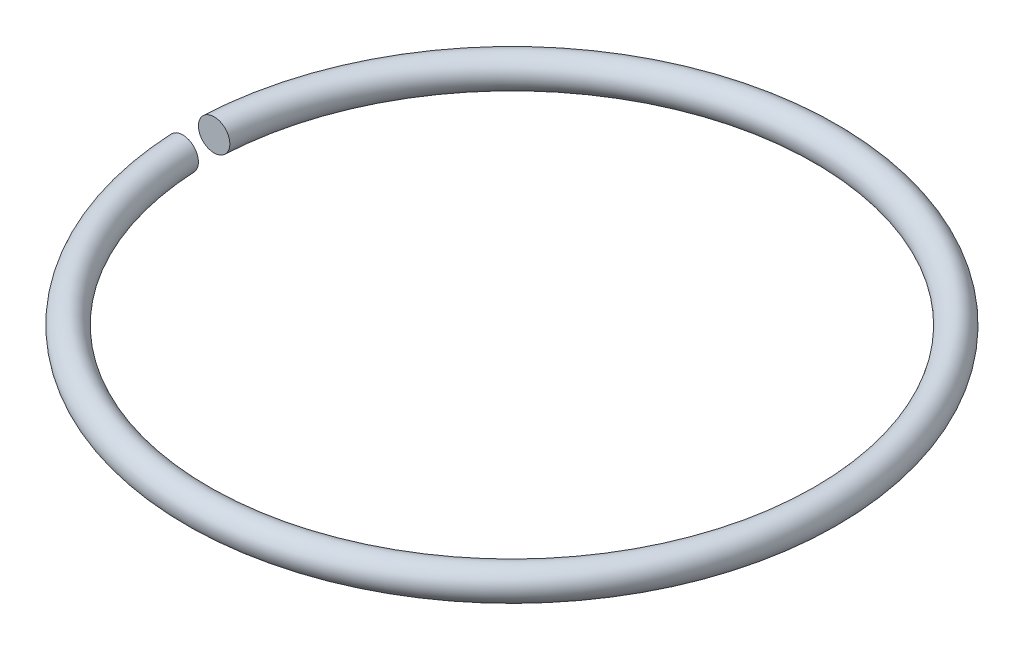
SolidWorks part; units mm, degrees
material "1.5805 (10NiCr5-4)"
ref_plane "Спереди" through (0, 0, 0) normal (0, 0, 1) x (1, 0, 0)
ref_plane "Сверху" through (0, 0, 0) normal (0, 1, 0) x (1, 0, 0)
ref_plane "Справа" through (0, 0, 0) normal (1, 0, 0) x (0, 0, -1)
sketch "Эскиз1" plane through (0, 0, 0) normal (0, 0, 1) x (1, 0, 0)
  line L0 (0, 0) -> (0, 5.376) construction
  circle A0 centre (-20, 1) radius 1
  dimension "D1" = 2
  dimension "D3" = 1
  dimension "D2" = 20
revolve "Повернуть1" add sketch "Эскиз1" angle 360 about L0
sketch "Эскиз2" plane through (0, 0, 0) normal (0, 1, 0) x (1, 0, 0)
  line L0 (0, 0) -> (-16.7656, 0) construction
  line L1 (-23.1189, 1) -> (-7.1672, 1)
  line L2 (-23.1189, 1) -> (-23.1189, -1)
  line L3 (-23.1189, -1) -> (-7.1672, -1)
  line L4 (-7.1672, 1) -> (-7.1672, -1)
  dimension "D1" = 1
  dimension "D2" = 1
extrude "Вырез-Вытянуть1" cut sketch "Эскиз2" against normal through all and the other way through all
ref_plane "Плоскость1" through (0, 0, 0) normal (0, -1, 0) x (-1, 0, 0)
